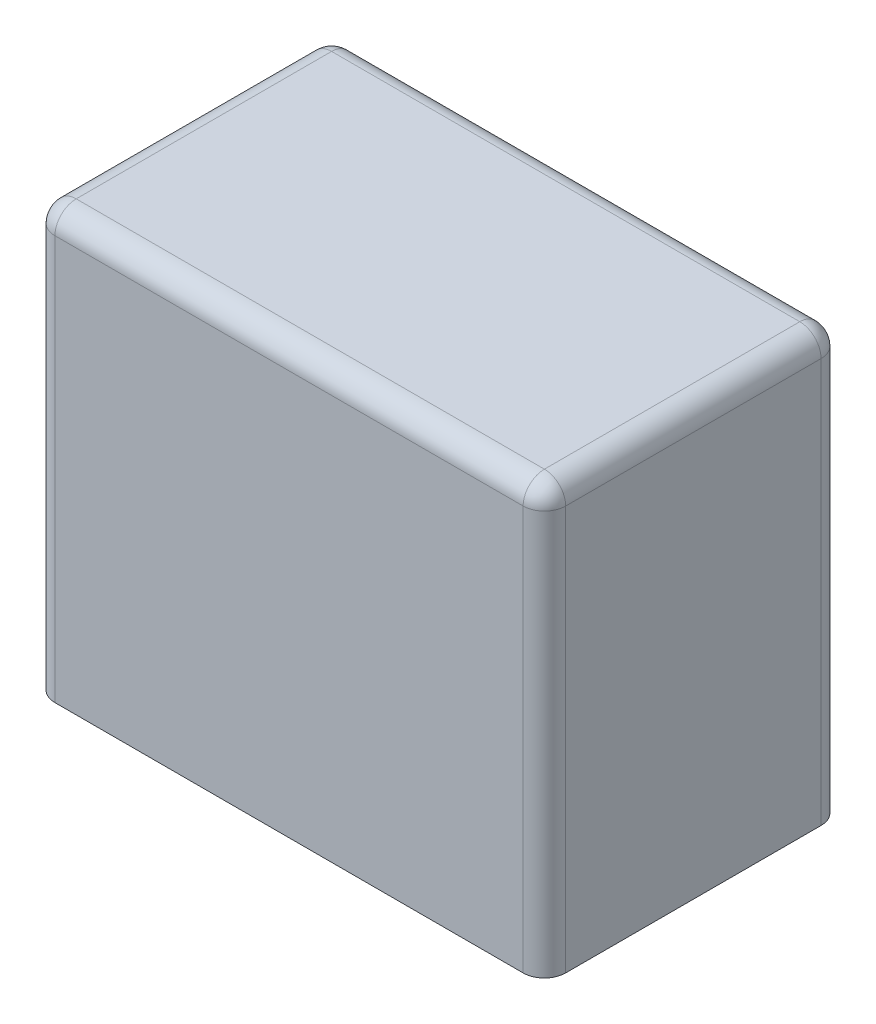
SolidWorks part; units mm, degrees
ref_plane "Front Plane" through (0, 0, 0) normal (0, 0, 1) x (1, 0, 0)
ref_plane "Top Plane" through (0, 0, 0) normal (0, 1, 0) x (1, 0, 0)
ref_plane "Right Plane" through (0, 0, 0) normal (1, 0, 0) x (0, 0, -1)
sketch "Sketch1" plane through (0, 0, 0) normal (0, 1, 0) x (1, 0, 0)
  line L1 (-12, -7) -> (12, -7)
  line L2 (-12, -7) -> (-12, 7)
  line L3 (-12, 7) -> (12, 7)
  line L4 (12, -7) -> (12, 7)
  line L5 (-12, -7) -> (12, 7) construction
  line L6 (-12, 7) -> (12, -7) construction
  point P0 (0, 0)
  dimension "D1" = 14
  dimension "D2" = 24
extrude "Boss-Extrude1" add sketch "Sketch1" along normal blind 20
fillet "Fillet1" radius 1 8 edges at (0, 20, 7) (-12, 20, 0) (0, 20, -7) (12, 20, 0) (-12, 10, -7) (12, 10, -7) (12, 10, 7) (-12, 10, 7)
